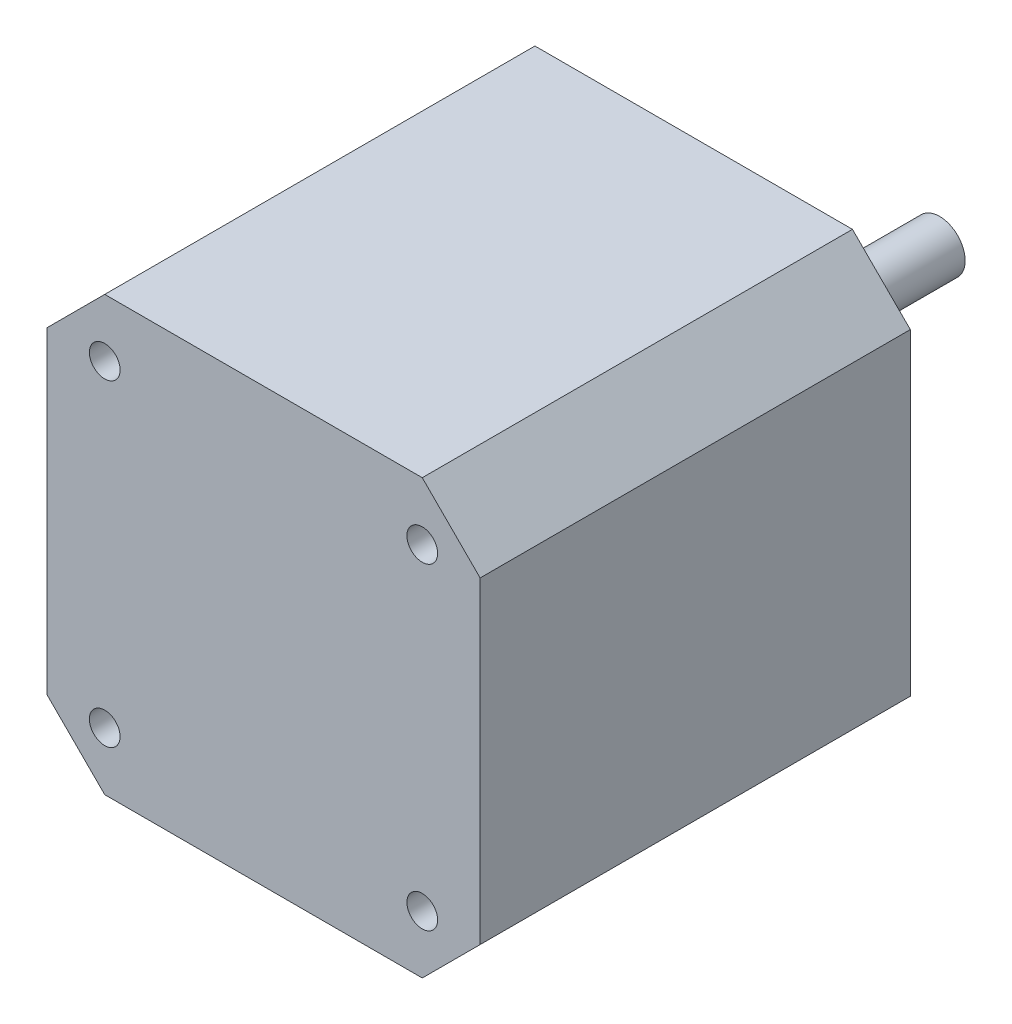
SolidWorks part; units mm, degrees
ref_plane "Front Plane" through (0, 0, 0) normal (0, 0, 1) x (1, 0, 0)
ref_plane "Top Plane" through (0, 0, 0) normal (0, 1, 0) x (1, 0, 0)
ref_plane "Right Plane" through (0, 0, 0) normal (1, 0, 0) x (0, 0, -1)
sketch "Sketch1" plane through (0, 0, 0) normal (0, 0, 1) x (1, 0, 0)
  line L0 (-15.5, 21.15) -> (-21.15, 15.5)
  line L1 (-15.5, -21.15) -> (15.5, -21.15)
  line L2 (-21.15, -15.5) -> (-21.15, 15.5)
  line L3 (-15.5, 21.15) -> (15.5, 21.15)
  line L4 (21.15, -15.5) -> (21.15, 15.5)
  line L13 (21.15, 15.5) -> (15.5, 21.15)
  line L14 (15.5, -21.15) -> (21.15, -15.5)
  line L15 (-21.15, -15.5) -> (-15.5, -21.15)
  circle A0 centre (15.5, 15.5) radius 1.5
  circle A1 centre (15.5, -15.5) radius 1.5
  circle A2 centre (-15.5, -15.5) radius 1.5
  circle A3 centre (-15.5, 15.5) radius 1.5
  point P0 (0, 0)
  point P6 (0, 0)
  point P21 (0, 0)
  point P30 (0, 0)
  dimension "D1" = 4
  dimension "D2" = 4
extrude "Boss-Extrude1" add sketch "Sketch1" along normal blind 42
sketch "Sketch3" plane through (0, 0, 0) normal (1, 0, 0) x (0, 0, -1)
  line L0 (0, 0) -> (24, 0)
  line L1 (24, 0) -> (24, 2.5)
  line L2 (24, 2.5) -> (2, 2.5)
  line L3 (2, 2.5) -> (2, 11)
  line L4 (2, 11) -> (0, 11)
  line L5 (0, 15.5) -> (0, -15.5) construction
  line L6 (0, 11) -> (0, 0)
revolve "Revolve1" add sketch "Sketch3" angle 360 about L0
